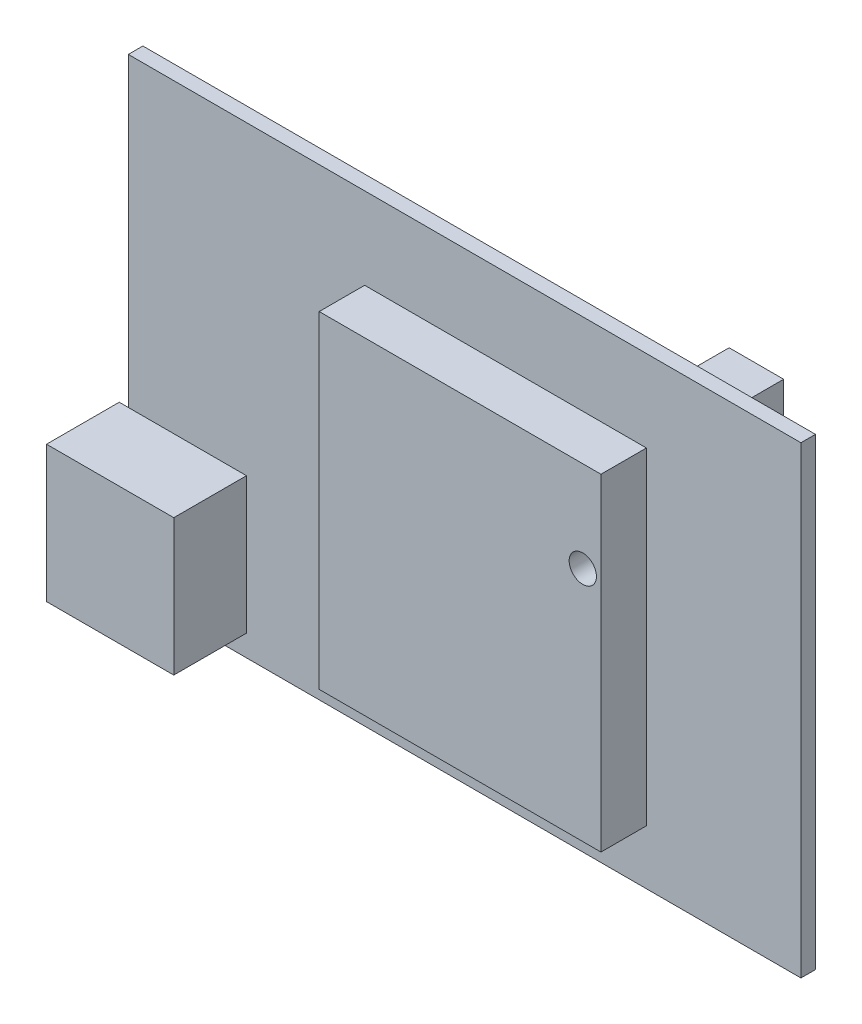
SolidWorks part; units mm, degrees
ref_plane "Front Plane" through (0, 0, 0) normal (0, 0, 1) x (1, 0, 0)
ref_plane "Top Plane" through (0, 0, 0) normal (0, 1, 0) x (1, 0, 0)
ref_plane "Right Plane" through (0, 0, 0) normal (1, 0, 0) x (0, 0, -1)
sketch "Sketch1" plane through (0, 0, 0) normal (0, 0, 1) x (1, 0, 0)
  line L1 (0, 0) -> (74, 0)
  line L2 (0, 0) -> (0, 51)
  line L3 (0, 51) -> (74, 51)
  line L4 (74, 0) -> (74, 51)
  dimension "D1" = 51
  dimension "D2" = 74
extrude "Boss-Extrude1" add sketch "Sketch1" along normal blind 1.6
sketch "Sketch2" plane through (0, 0, 1.6) normal (0, 0, 1) x (1, 0, 0)
  line L0 (0, 0) -> (74, 0) construction
  line L1 (26, 42) -> (57, 42)
  line L2 (26, 42) -> (26, 6)
  line L3 (26, 6) -> (57, 6)
  line L4 (57, 42) -> (57, 6)
  line L5 (74, 0) -> (74, 51) construction
  dimension "D1" = 36
  dimension "D2" = 31
  dimension "D3" = 6
  dimension "D4" = 17
extrude "Boss-Extrude2" add sketch "Sketch2" along normal blind 5
sketch "Sketch3" plane through (0, 0, 1.6) normal (0, 0, 1) x (1, 0, 0)
  line L0 (0, 0) -> (74, 0) construction
  line L1 (-1, 17.36) -> (13, 17.36)
  line L2 (-1, 17.36) -> (-1, 2.36)
  line L3 (-1, 2.36) -> (13, 2.36)
  line L4 (13, 17.36) -> (13, 2.36)
  line L5 (0, 51) -> (0, 0) construction
  dimension "D1" = 2.36
  dimension "D2" = 14
  dimension "D3" = 1
  dimension "D4" = 15
extrude "Boss-Extrude3" add sketch "Sketch3" along normal blind 8
sketch "Sketch4" plane through (0, 0, 0) normal (0, 0, -1) x (-1, 0, 0)
  line L0 (-74, 0) -> (-74, 51) construction
  line L1 (-66, 50) -> (-60, 50)
  line L2 (-66, 50) -> (-66, 1)
  line L3 (-66, 1) -> (-60, 1)
  line L4 (-60, 50) -> (-60, 1)
  line L5 (-74, 51) -> (0, 51) construction
  line L6 (0, 0) -> (-74, 0) construction
  dimension "D1" = 8
  dimension "D2" = 1
  dimension "D3" = 1
  dimension "D4" = 6
extrude "Boss-Extrude4" add sketch "Sketch4" along normal blind 4.5
sketch "Sketch6" plane through (0, 0, 1.6) normal (0, 0, 1) x (1, 0, 0)
  line L0 (68.5, 51) -> (0, 51) construction
  line L1 (74, 0) -> (74, 51) construction
  line L2 (0, 51) -> (0, 17.36) construction
  circle A0 centre (55, 32) radius 1.5
  circle A1 centre (24, 25.5) radius 1.5
  dimension "D3" = 24
  dimension "D4" = 25.5
  dimension "D1" = 19
  dimension "D2" = 19
extrude "Cut-Extrude1" cut sketch "Sketch6" against normal through all and the other way blind 8.5
